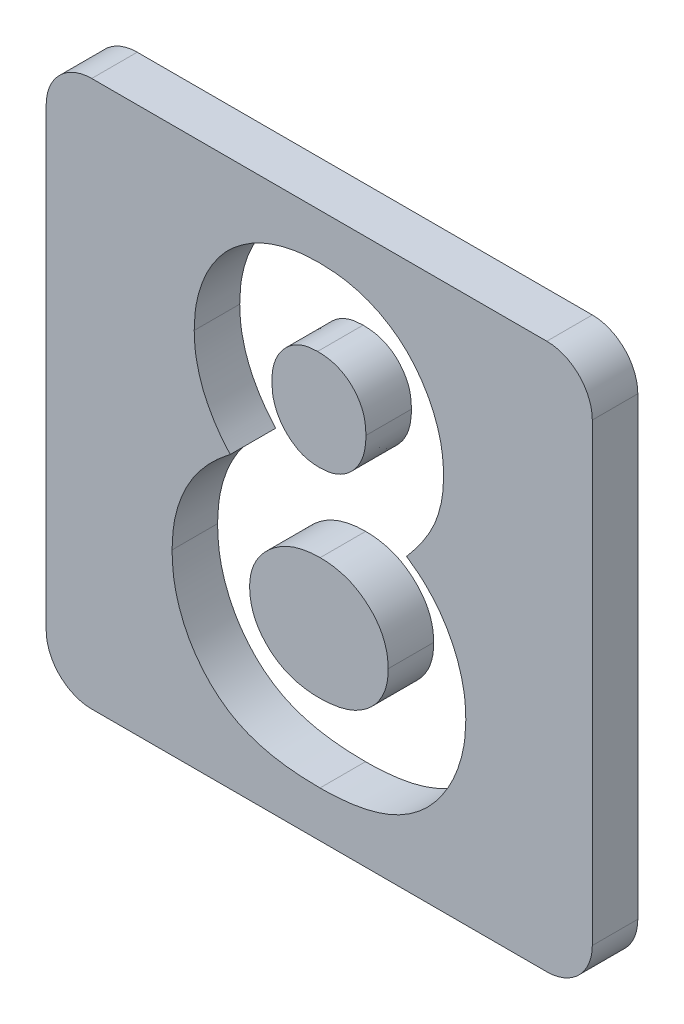
SolidWorks part; units mm, degrees
ref_plane "Front Plane" through (0, 0, 0) normal (0, 0, 1) x (1, 0, 0)
ref_plane "Top Plane" through (0, 0, 0) normal (0, 1, 0) x (1, 0, 0)
ref_plane "Right Plane" through (0, 0, 0) normal (1, 0, 0) x (0, 0, -1)
sketch "Sketch1" plane through (0, 0, 0) normal (0, 0, 1) x (1, 0, 0)
  line L1 (-50, 60) -> (50, 60)
  line L2 (-60, 50) -> (-60, -50)
  line L3 (-50, -60) -> (50, -60)
  line L4 (60, 50) -> (60, -50)
  line L5 (-60, 60) -> (60, -60) construction
  line L6 (-60, -60) -> (60, 60) construction
  arc A0 (-60, -50) -> (-50, -60) centre (-50, -50) ccw
  arc A1 (50, -60) -> (60, -50) centre (50, -50) ccw
  arc A2 (50, 60) -> (60, 50) centre (50, 50) cw
  arc A3 (-50, 60) -> (-60, 50) centre (-50, 50) ccw
  point P0 (0, 0)
  dimension "D3" = 10
  dimension "D1" = 120
  dimension "D2" = 120
extrude "Boss-Extrude1" add sketch "Sketch1" along normal blind 10 contours A3 L2 A0 L3 A1 L4 A2 L1
sketch "Sketch2" plane through (0, 0, 10) normal (0, 0, 1) x (1, 0, 0)
  line L0 (0, 0) -> (0, 40) construction
  line L1 (-50, 50) -> (50, 50) construction
  line L2 (-50, 50) -> (-50, -50) construction
  line L3 (-50, -50) -> (50, -50) construction
  line L4 (50, 50) -> (50, -50) construction
  line L5 (-50, 50) -> (50, -50) construction
  line L6 (-50, -50) -> (50, 50) construction
  line L7 (0, 40) -> (-40, 40) construction
  line L8 (-40, 40) -> (-40, 0) construction
  line L9 (-40, 0) -> (0, 0) construction
  line L11 (0, 20) -> (-20, 20) construction
  line L12 (-20, 40) -> (-20, 20) construction
  circle A0 centre (0, 40) radius 4 construction
  circle A1 centre (0, 20) radius 4 construction
  circle A2 centre (0, 0) radius 4 construction
  circle A3 centre (-20, 20) radius 4 construction
  circle A4 centre (-20, 40) radius 4 construction
  circle A5 centre (-40, 40) radius 4 construction
  circle A6 centre (0, 0) radius 4 construction
  circle A7 centre (20, 0) radius 4 construction
  circle A8 centre (40, 0) radius 4 construction
  circle A9 centre (40, 20) radius 4 construction
  circle A10 centre (40, 40) radius 4 construction
  circle A11 centre (20, 20) radius 4 construction
  circle A12 centre (0, 0) radius 4 construction
  circle A13 centre (0, -20) radius 4 construction
  circle A14 centre (0, -40) radius 4 construction
  circle A15 centre (20, -40) radius 4 construction
  circle A16 centre (40, -40) radius 4 construction
  circle A17 centre (20, -20) radius 4 construction
  circle A18 centre (0, 0) radius 4 construction
  circle A19 centre (-20, 0) radius 4 construction
  circle A20 centre (-40, 0) radius 4 construction
  circle A21 centre (-40, -20) radius 4 construction
  circle A22 centre (-40, -40) radius 4 construction
  circle A23 centre (-20, -20) radius 4 construction
  text T0 "8" font "Century Gothic" height 95
  point P0 (0, 0)
  point P55 (0, 0)
  dimension "D4" = 8
  dimension "D1" = 100
  dimension "D2" = 100
  dimension "D3" = 40
  dimension "D5" = 4
extrude "Cut-Extrude7" cut sketch "Sketch2" against normal blind 10
